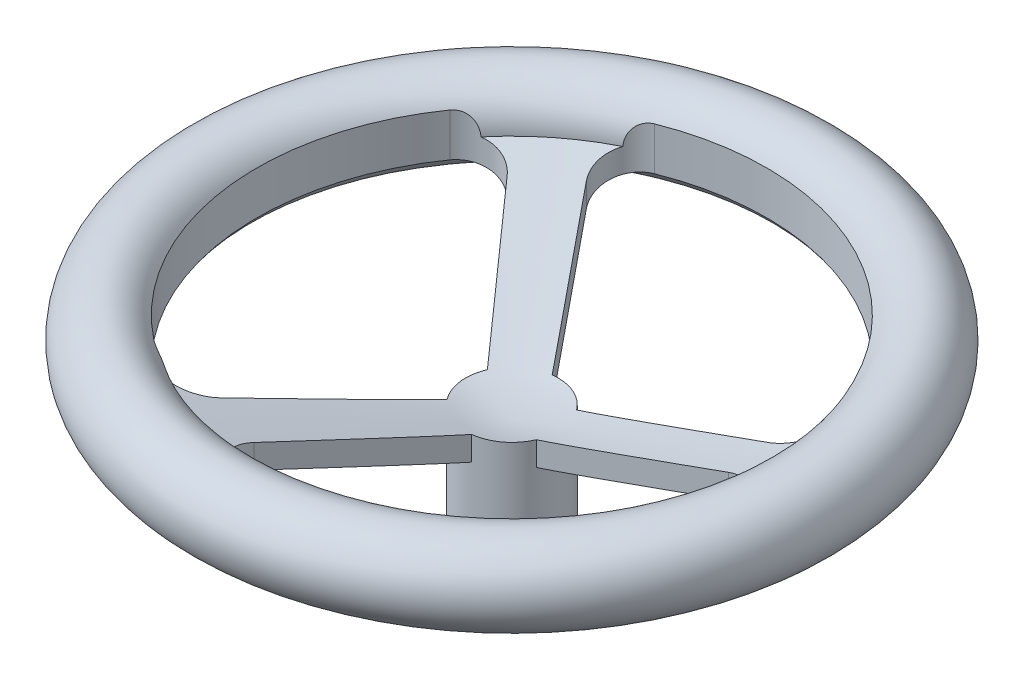
SolidWorks part; units mm, degrees
ref_plane "Front Plane" through (0, 0, 0) normal (0, 0, 1) x (1, 0, 0)
ref_plane "Top Plane" through (0, 0, 0) normal (0, 1, 0) x (1, 0, 0)
ref_plane "Right Plane" through (0, 0, 0) normal (1, 0, 0) x (0, 0, -1)
sketch "Sketch1" plane through (0, 0, 0) normal (0, 0, 1) x (1, 0, 0)
  line L0 (0, 122.2038) -> (0, -120.1267) construction
  line L1 (20, -100.7402) -> (20, -69.7153)
  line L2 (20, -69.7153) -> (110.1988, -44.4597)
  line L4 (107.5025, -34.83) -> (0, -64.9307)
  line L5 (0, -64.9307) -> (0, -78.0581)
  line L6 (0, -78.0581) -> (12.5, -78.0581)
  line L7 (12.5, -78.0581) -> (12.5, -100.7402)
  line L8 (12.5, -100.7402) -> (20, -100.7402)
  arc A0 (110.1988, -44.4597) -> (107.5025, -34.83) centre (125, -35.123) ccw
  dimension "D5" = 35
  dimension "D1" = 250
  dimension "D2" = 25
  dimension "D3" = 40
  dimension "D4" = 10
revolve "Revolve1" add sketch "Sketch1" angle 360 about L0
sketch "Sketch3" plane through (0, -100.7402, 0) normal (0, -1, 0) x (1, 0, 0)
  line L0 (-15.9821, 12.0238) -> (-45.1597, 80.6127)
  line L3 (15.9821, -12.0238) -> (89.9706, -21.0497)
  line L4 (2.4219, 19.8528) -> (-21.1852, 90.1696)
  line L6 (18.404, 7.829) -> (92.3925, -1.1969)
  line L7 (-18.404, -7.829) -> (-66.4611, -64.4348)
  line L8 (-2.4219, -19.8528) -> (-47.2328, -79.4158)
  arc A0 (109.0529, 15.8502) -> (-8.0627, 109.9034) centre (0, 0) ccw
  circle A1 centre (0, 0) radius 110.1988 construction
  arc A2 (18.404, 7.829) -> (2.4219, 19.8528) centre (0, 0) ccw
  arc A3 (92.3925, -1.1969) -> (109.0529, 15.8502) centre (94.2089, 13.6927) ccw
  arc A4 (-2.4219, -19.8528) -> (15.9821, -12.0238) centre (0, 0) ccw
  arc A5 (-15.9821, 12.0238) -> (-18.404, -7.829) centre (0, 0) ccw
  arc A6 (-40.7998, -102.3677) -> (102.0442, -41.6021) centre (0, 0) ccw
  arc A7 (-68.2531, 86.5175) -> (-90.1696, -63.3499) centre (0, 0) ccw
  arc A8 (-47.2328, -79.4158) -> (-40.7998, -102.3677) centre (-35.2462, -88.4336) ccw
  arc A9 (-45.1597, 80.6127) -> (-68.2531, 86.5175) centre (-58.9627, 74.7409) ccw
  arc A10 (-90.1696, -63.3499) -> (-66.4611, -64.4348) centre (-77.8959, -54.7268) ccw
  arc A11 (-8.0627, 109.9034) -> (-21.1852, 90.1696) centre (-6.9652, 94.9436) ccw
  arc A12 (102.0442, -41.6021) -> (89.9706, -21.0497) centre (88.1542, -35.9394) ccw
  point P7 (-43.1374, 101.4048)
  point P12 (0, 0)
  point P24 (0, 0)
  point P29 (0, 0)
  dimension "D1" = 30
  dimension "D4" = 30
  dimension "D5" = 30
  dimension "D6" = 30
  dimension "D2" = 10
  dimension "D3" = 3
extrude "Cut-Extrude1" cut sketch "Sketch3" against normal through all
